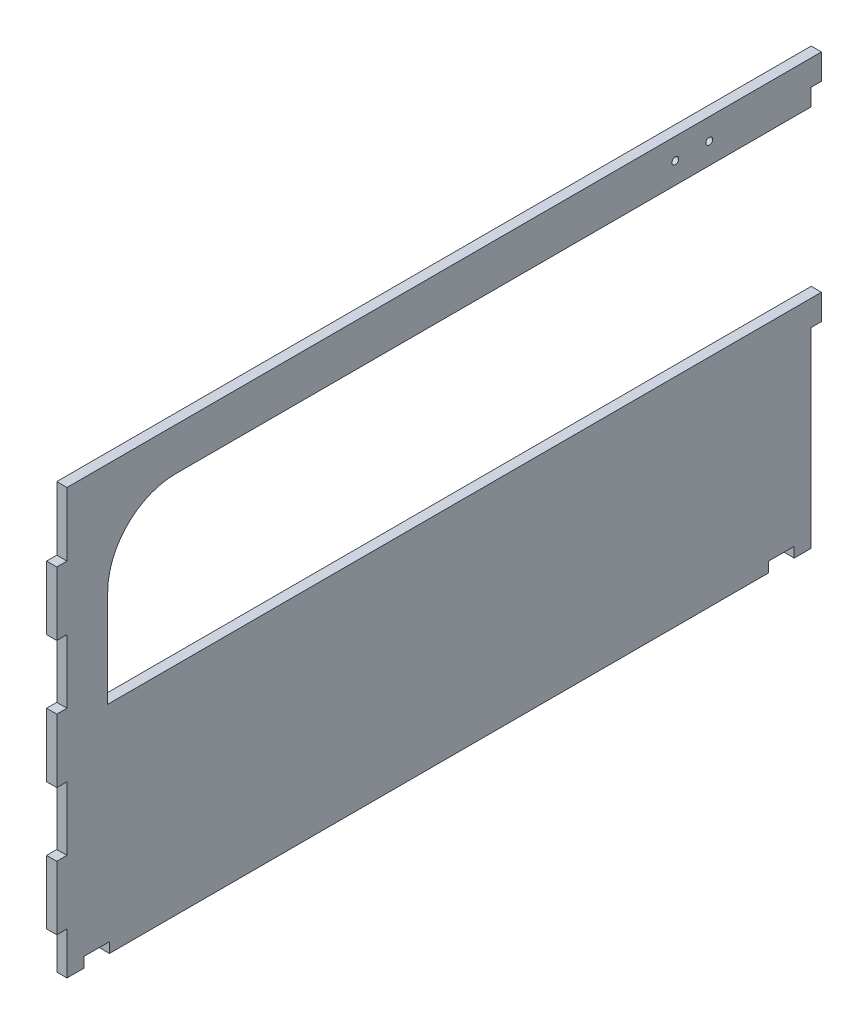
SolidWorks part; units mm, degrees
ref_plane "Front" through (0, 0, 0) normal (0, 0, 1) x (1, 0, 0)
ref_plane "Top" through (0, 0, 0) normal (0, 1, 0) x (1, 0, 0)
ref_plane "Right" through (0, 0, 0) normal (1, 0, 0) x (0, 0, -1)
sketch "Sketch1" plane through (0, 0, 0) normal (1, 0, 0) x (0, 0, -1)
  line L0 (450, 225) -> (450, 250)
  line L1 (0, 0) -> (450, 0)
  line L2 (0, 0) -> (0, 250)
  line L3 (0, 250) -> (450, 250)
  line L4 (450, 0) -> (450, 127.5)
  line L5 (450, 225) -> (30, 225)
  line L7 (450, 127.5) -> (30, 127.5)
  line L8 (30, 225) -> (30, 127.5)
  dimension "D1" = 420
  dimension "D2" = 250
  dimension "D3" = 127.5
  dimension "D4" = 25
  dimension "D5" = 30
extrude "Boss-Extrude1" add sketch "Sketch1" along normal blind 6
sketch "Sketch2" plane through (6, 0, 0) normal (1, 0, 0) x (0, 0, -1)
  line L1 (0, 250) -> (6, 250)
  line L2 (0, 250) -> (0, 212.5)
  line L3 (0, 212.5) -> (6, 212.5)
  line L4 (6, 250) -> (6, 212.5)
  dimension "D1" = 6
  dimension "D2" = 37.5
extrude "Cut-Extrude1" cut sketch "Sketch2" against normal blind 6
pattern_linear "LPattern1" count 4 spacing 75 along (0, -1, 0) of "Cut-Extrude1"
fillet "Fillet1" radius 40 1 edges at (3, 225, -30)
sketch "Sketch3" plane through (0, 0, 0) normal (-1, 0, 0) x (0, 0, 1)
  line L0 (-450, 0) -> (-450, 127.5) construction
  line L1 (-450, 235) -> (-444, 235)
  line L2 (-450, 235) -> (-450, 225)
  line L3 (-450, 225) -> (-444, 225)
  line L4 (-444, 235) -> (-444, 225)
  line L5 (-70, 225) -> (-450, 225) construction
  line L7 (-450, 112.5) -> (-444, 112.5)
  line L8 (-450, 112.5) -> (-450, 0)
  line L9 (-450, 0) -> (-444, 0)
  line L10 (-444, 112.5) -> (-444, 0)
  line L12 (-450, 225) -> (-450, 250) construction
  line L13 (-450, 127.5) -> (-30, 127.5) construction
  line L14 (-6, 0) -> (-450, 0) construction
  point P4 (-444, 127.5)
  point P13 (-444, 113.4902)
  point P18 (-444, 0)
  dimension "D1" = 6
  dimension "D2" = 10
  dimension "D4" = 15
extrude "Cut-Extrude2" cut sketch "Sketch3" against normal through all
sketch "Sketch4" plane through (0, 0, 0) normal (-1, 0, 0) x (0, 0, 1)
  line L0 (-6, 0) -> (-444, 0) construction
  line L1 (-16, 0) -> (-31, 0)
  line L2 (-16, 0) -> (-16, 6)
  line L3 (-16, 6) -> (-31, 6)
  line L4 (-31, 0) -> (-31, 6)
  line L5 (-6, 62.5) -> (-6, 100) construction
  line L6 (-6, 0) -> (-444, 0) construction
  line L7 (-434, 0) -> (-419, 0)
  line L8 (-434, 0) -> (-434, 6)
  line L9 (-434, 6) -> (-419, 6)
  line L10 (-419, 0) -> (-419, 6)
  line L11 (-444, 0) -> (-444, 112.5) construction
  dimension "D1" = 10
  dimension "D2" = 15
  dimension "D3" = 6
  dimension "D4" = 10
extrude "Cut-Extrude3" cut sketch "Sketch4" against normal through all
sketch "Sketch5" plane through (0, 0, 0) normal (-1, 0, 0) x (0, 0, 1)
  line L0 (-450, 235) -> (-450, 250) construction
  line L1 (-450, 250) -> (-6, 250) construction
  circle A0 centre (-384, 237.5) radius 2
  circle A1 centre (-364, 237.5) radius 2
  point P8 (0, 0)
  dimension "D3" = 4
  dimension "D1" = 66
  dimension "D2" = 12.5
  dimension "D4" = 20
extrude "Cut-Extrude4" cut sketch "Sketch5" against normal through all
